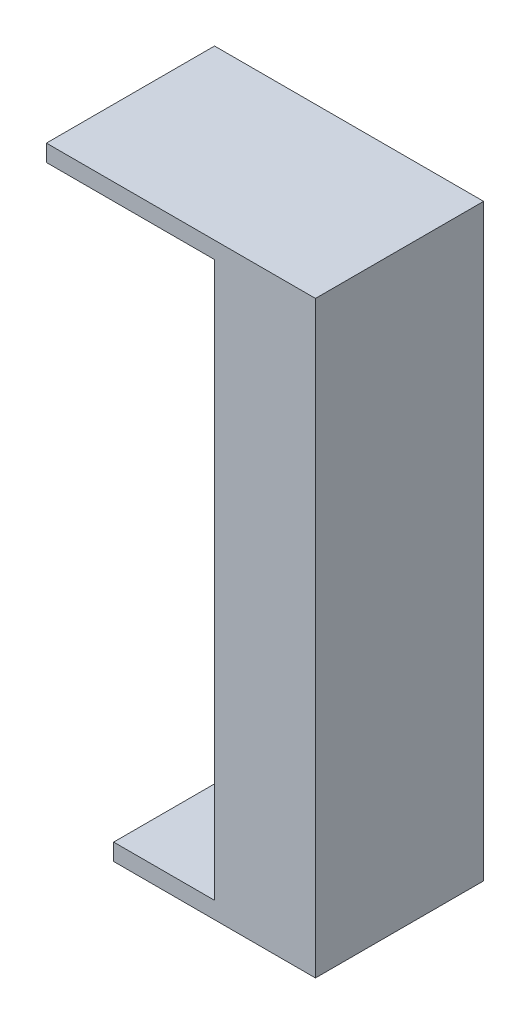
SolidWorks part; units mm, degrees
ref_plane "Alzado" through (0, 0, 0) normal (0, 0, 1) x (1, 0, 0)
ref_plane "Planta" through (0, 0, 0) normal (0, 1, 0) x (1, 0, 0)
ref_plane "Vista lateral" through (0, 0, 0) normal (1, 0, 0) x (0, 0, -1)
sketch "Croquis1" plane through (0, 0, 0) normal (0, 0, 1) x (1, 0, 0)
  line L0 (-25, 87.5) -> (-25, 82.5)
  line L1 (-25, 82.5) -> (25, 82.5)
  line L2 (25, 82.5) -> (25, -82.5)
  line L3 (25, -82.5) -> (-5, -82.5)
  line L4 (-5, -82.5) -> (-5, -87.5)
  line L5 (-5, -87.5) -> (55, -87.5)
  line L6 (55, -87.5) -> (55, 87.5)
  line L7 (55, 87.5) -> (-25, 87.5)
  line L8 (-148.2189, 0) -> (199.321, 0) construction
  line L9 (0, 82.5) -> (0, -57.5) construction
  point P11 (55, -62.5)
  point P14 (-5, -62.5)
  dimension "D1" = 165
  dimension "D2" = 30
  dimension "D3" = 5
  dimension "D4" = 5
  dimension "D5" = 50
  dimension "D6" = 30
extrude "Saliente-Extruir1" add sketch "Croquis1" along normal mid plane 50
